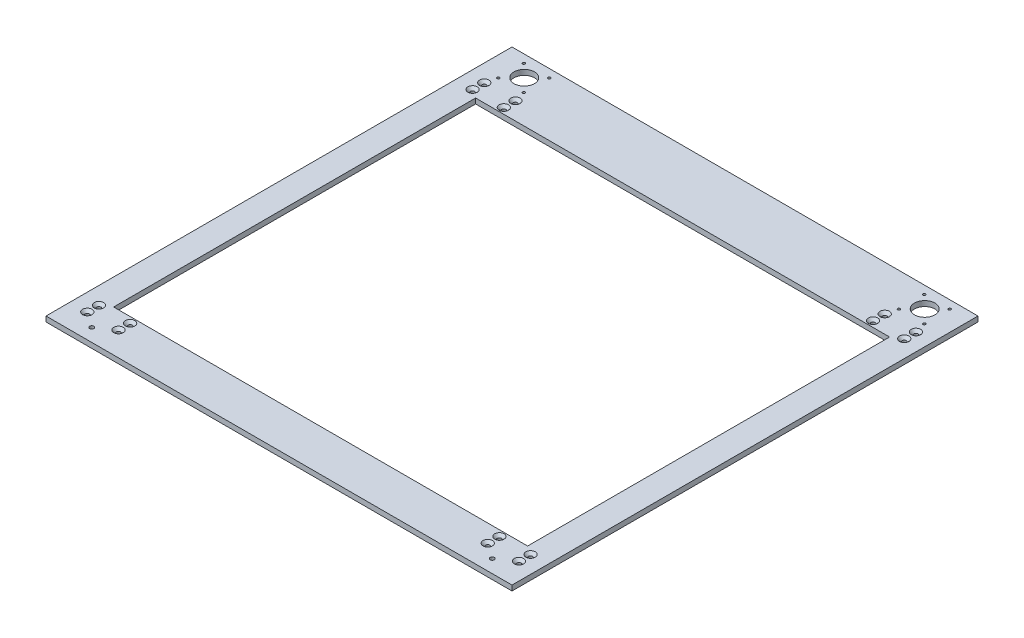
SolidWorks part; units mm, degrees
material "6061 Alloy"
ref_plane "Front Plane" through (0, 0, 0) normal (0, 0, 1) x (1, 0, 0)
ref_plane "Top Plane" through (0, 0, 0) normal (0, 1, 0) x (1, 0, 0)
ref_plane "Right Plane" through (0, 0, 0) normal (1, 0, 0) x (0, 0, -1)
sketch "Sketch1" plane through (0, 0, 0) normal (0, 1, 0) x (1, 0, 0)
  line L1 (-284.48, -284.48) -> (284.48, -284.48)
  line L2 (-284.48, -284.48) -> (-284.48, 284.48)
  line L3 (-284.48, 284.48) -> (284.48, 284.48)
  line L4 (284.48, -284.48) -> (284.48, 284.48)
  line L5 (-284.48, -284.48) -> (284.48, 284.48) construction
  line L6 (-284.48, 284.48) -> (284.48, -284.48) construction
  point P0 (0, 0)
  dimension "D1" = 568.96
  dimension "D2" = 568.96
extrude "Boss-Extrude1" add sketch "Sketch1" along normal mid plane 6.35
sketch "Sketch3" plane through (0, 3.175, 0) normal (0, 1, 0) x (1, 0, 0)
  line L1 (-317.1581, 0) -> (318.0113, 0) construction
  line L2 (-284.48, -284.48) -> (284.48, -284.48) construction
  line L3 (0, 335.6648) -> (0, -341.413) construction
  circle A0 centre (-244.475, 259.4) radius 12.5
  circle A1 centre (-259.969, 274.4) radius 1.55
  circle A2 centre (-228.981, 274.4) radius 1.55
  circle A3 centre (-228.981, 243.412) radius 1.55
  circle A4 centre (-259.969, 243.412) radius 1.55
  circle A5 centre (-244.475, -268.605) radius 2.55
  dimension "D1" = 25
  dimension "D4" = 3.1
  dimension "D8" = 30.988
  dimension "D2" = 15
  dimension "D3" = 15.494
  dimension "D9" = 5.1
  dimension "D11" = 0
  dimension "D6" = 244.475
  dimension "D5" = 259.4
  dimension "D10" = 15.875
  dimension "D7" = 4
extrude "Cut-Extrude2" cut sketch "Sketch3" against normal up to surface (6.35 mm away) up to face at (0, -3.175, 0)
mirror "Mirror2" about plane through (0, 0, 0) normal (1, 0, 0) of "Cut-Extrude2"
sketch "Sketch4" plane through (0, 3.175, 0) normal (0, 1, 0) x (1, 0, 0)
  line L0 (284.48, 284.48) -> (-284.48, 284.48) construction
  line L1 (-252.73, -233.68) -> (252.73, -233.68)
  line L2 (-252.73, -233.68) -> (-252.73, 208.28)
  line L3 (-252.73, 208.28) -> (252.73, 208.28)
  line L4 (252.73, -233.68) -> (252.73, 208.28)
  line L5 (-244.475, 259.4) -> (-244.475, 208.28) construction
  line L6 (0, 284.48) -> (0, -284.48) construction
  line L7 (-284.48, -284.48) -> (284.48, -284.48) construction
  line L8 (252.73, -12.7) -> (-252.73, -12.7) construction
  circle A0 centre (-225.425, 215.4238) radius 2.55
  circle A1 centre (-263.525, 215.4238) radius 2.55
  circle A2 centre (-263.525, 229.6478) radius 2.55
  circle A3 centre (-225.425, 229.6478) radius 2.55
  circle A4 centre (263.525, 229.6478) radius 2.55
  circle A5 centre (263.525, 215.4238) radius 2.55
  circle A6 centre (225.425, 215.4238) radius 2.55
  circle A7 centre (225.425, 229.6478) radius 2.55
  circle A8 centre (225.425, -240.8237) radius 2.55
  circle A9 centre (225.425, -255.0477) radius 2.55
  circle A10 centre (263.525, -240.8237) radius 2.55
  circle A11 centre (263.525, -255.0477) radius 2.55
  circle A12 centre (-225.425, -240.8237) radius 2.55
  circle A13 centre (-263.525, -240.8237) radius 2.55
  circle A14 centre (-225.425, -255.0478) radius 2.55
  circle A15 centre (-263.525, -255.0478) radius 2.55
  dimension "D5" = 5.1
  dimension "D9" = 14.224
  dimension "D1" = 505.46
  dimension "D2" = 441.96
  dimension "D3" = 76.2
  dimension "D4" = 252.73
  dimension "D6" = 7.1437
  dimension "D7" = 19.05
  dimension "D8" = 2
extrude "Cut-Extrude4" cut sketch "Sketch4" against normal up to surface (6.35 mm away) up to face at (228.981, -3.175, -244.962)
ref_plane "Plane1" through (0, 0, 12.7) normal (0, 0, 1) x (1, 0, 0)
chamfer "Chamfer1" distance 3.2 angle 45 16 edges at (-225.425, 3.175, 252.4978) (-263.525, 3.175, 257.5978) (-225.425, 3.175, 238.2738) (-263.525, 3.175, 243.3738) (225.425, 3.175, 257.5977) (225.425, 3.175, 243.3737) (263.525, 3.175, 252.4977) (263.525, 3.175, 238.2737) (225.425, 3.175, -217.9738) (263.525, 3.175, -212.8738) (263.525, 3.175, -227.0978) (225.425, 3.175, -232.1978) (-263.525, 3.175, -232.1978) (-263.525, 3.175, -217.9738) (-225.425, 3.175, -212.8738) (-225.425, 3.175, -227.0978)
equation "\"D2@Sketch1\"=\"D1@Sketch1\""
equation "\"D1@Sketch4\"=\"D1@Sketch1\"-2.5"
equation "\"D2@Sketch4\"=\"D2@Sketch1\"-5.0"
equation "\"D4@Sketch4\"=\"D1@Sketch4\"/2"
equation "\"D3@Sketch3\"=\"D8@Sketch3\"/2"
